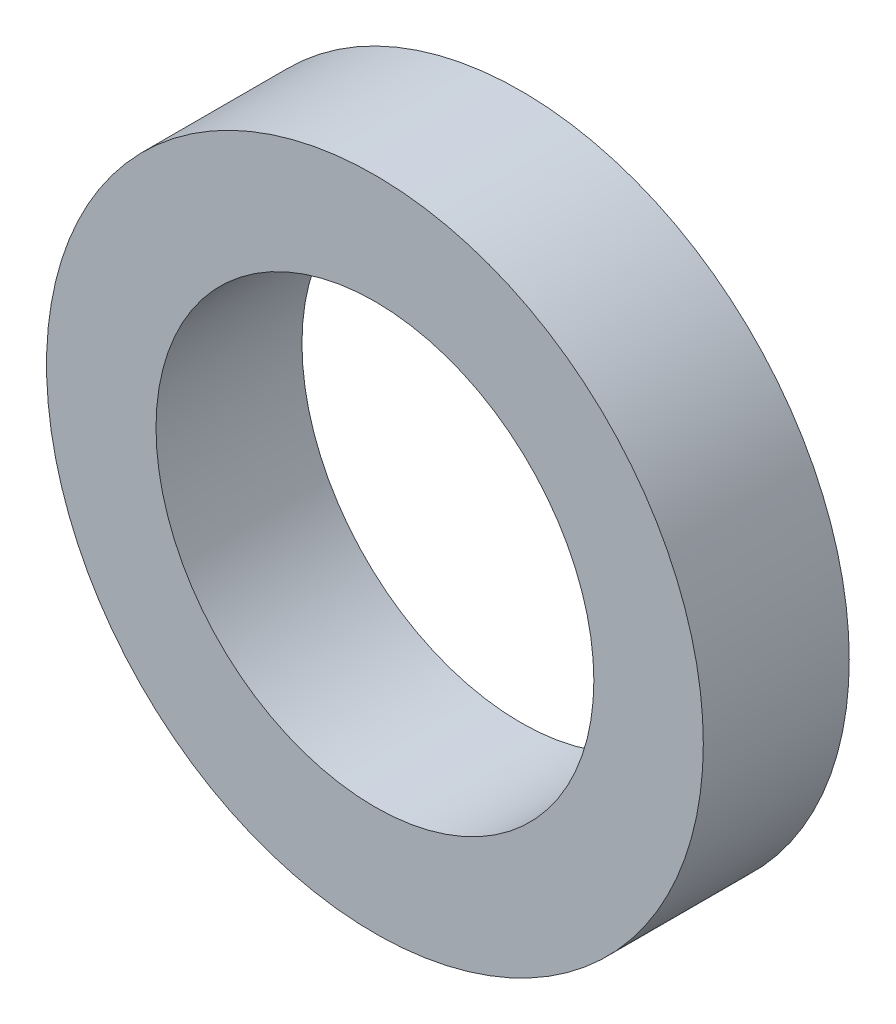
SolidWorks part; units mm, degrees
material "ABS"
ref_plane "前视基准面" through (0, 0, 0) normal (0, 0, 1) x (1, 0, 0)
ref_plane "上视基准面" through (0, 0, 0) normal (0, 1, 0) x (1, 0, 0)
ref_plane "右视基准面" through (0, 0, 0) normal (1, 0, 0) x (0, 0, -1)
sketch "草图1" plane through (0, 0, 0) normal (0, 0, 1) x (1, 0, 0)
  circle A0 centre (0, 0) radius 3
  circle A1 centre (0, 0) radius 4.5
  dimension "D1" = 6
  dimension "D2" = 9
extrude "凸台-拉伸1" add sketch "草图1" along normal blind 2
